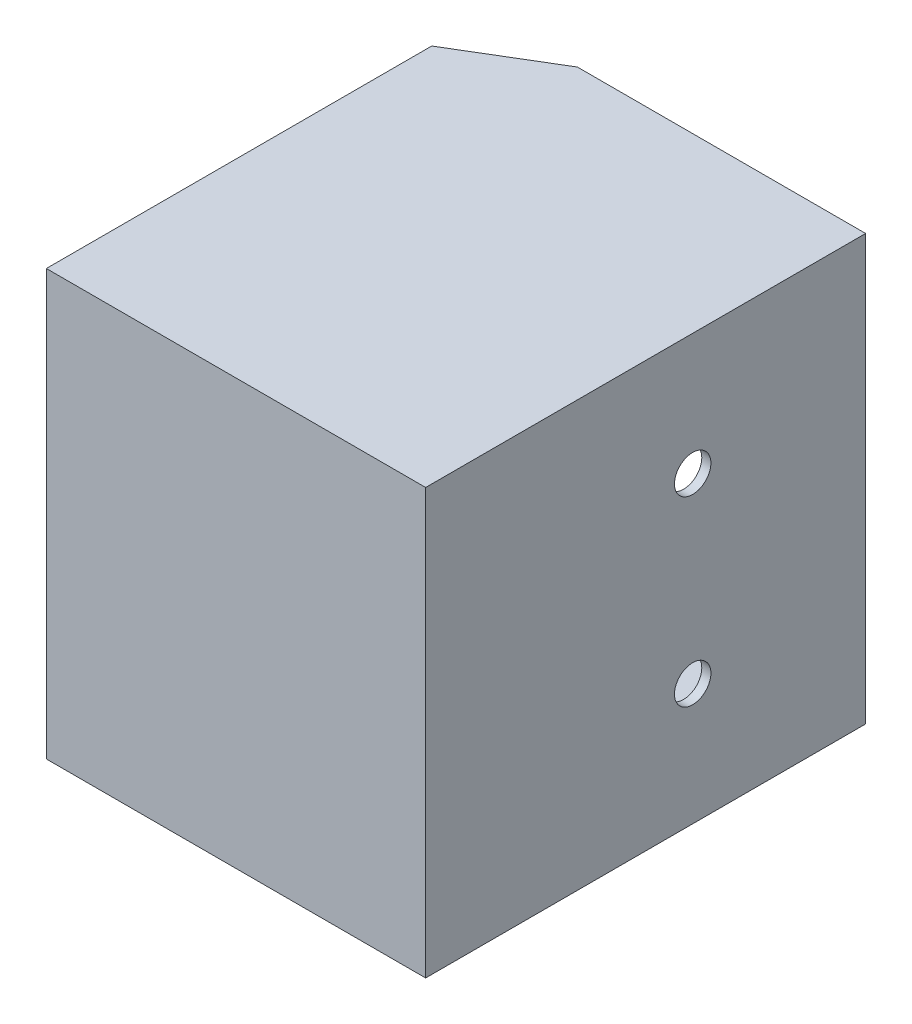
SolidWorks part; units mm, degrees
ref_plane "Front Plane" through (0, 0, 0) normal (0, 0, 1) x (1, 0, 0)
ref_plane "Top Plane" through (0, 0, 0) normal (0, 1, 0) x (1, 0, 0)
ref_plane "Right Plane" through (0, 0, 0) normal (1, 0, 0) x (0, 0, -1)
ref_plane "PL_Front_base" through (67, 0, 0) normal (1, 0, 0) x (0, 0, -1)
sketch "SK_Front" plane through (67, 0, 0) normal (1, 0, 0) x (0, 0, -1)
  line L0 (15, -70) -> (15, 70)
  line L1 (15, 70) -> (-130, 70)
  line L2 (-130, 70) -> (-130, -70)
  line L3 (-130, -70) -> (15, -70)
  circle A0 centre (-42, 30) radius 6
  circle A1 centre (-42, -30) radius 6
  dimension "D9_SK_Front" = 12
  dimension "D12_SK_Front" = 12
  dimension "P1" = 15
  dimension "P2" = 70
  dimension "P3" = 15
  dimension "P4" = 70
  dimension "P5" = 130
  dimension "P6" = 70
  dimension "P7" = 130
  dimension "P8" = 70
  dimension "P10" = 42
  dimension "P11" = 30
  dimension "P13" = 42
  dimension "P14" = 30
extrude "Front" add sketch "SK_Front" along normal blind 3
ref_plane "PL_Back_base" through (-55, 0, 0) normal (1, 0, 0) x (0, 0, -1)
sketch "SK_Back" plane through (-55, 0, 0) normal (1, 0, 0) x (0, 0, -1)
  line L0 (-3, -70) -> (-3, 70)
  line L1 (-3, 70) -> (-130, 70)
  line L2 (-130, 70) -> (-130, -70)
  line L3 (-130, -70) -> (-3, -70)
  dimension "P1" = 3
  dimension "P2" = 70
  dimension "P3" = 3
  dimension "P4" = 70
  dimension "P5" = 130
  dimension "P6" = 70
  dimension "P7" = 130
  dimension "P8" = 70
extrude "Back" add sketch "SK_Back" along normal blind 3
ref_plane "PL_Top_base" through (0, 0, 127) normal (0, 0, 1) x (1, 0, 0)
sketch "SK_Top" plane through (0, 0, 127) normal (0, 0, 1) x (1, 0, 0)
  line L0 (-55, -70) -> (70, -70)
  line L1 (70, -70) -> (70, 70)
  line L2 (70, 70) -> (-55, 70)
  line L3 (-55, 70) -> (-55, -70)
  dimension "P1" = 55
  dimension "P2" = 70
  dimension "P3" = 70
  dimension "P4" = 70
  dimension "P5" = 70
  dimension "P6" = 70
  dimension "P7" = 55
  dimension "P8" = 70
extrude "Top" add sketch "SK_Top" along normal blind 3
ref_plane "PL_Side_L_base" through (0, 67, 0) normal (0, 1, 0) x (1, 0, 0)
sketch "SK_Side_L" plane through (0, 67, 0) normal (0, 1, 0) x (1, 0, 0)
  line L0 (-25, 15) -> (70, 15)
  line L1 (70, 15) -> (70, -130)
  line L2 (70, -130) -> (-55, -130)
  line L3 (-55, -130) -> (-55, -3)
  line L4 (-55, -3) -> (-25, 15)
  dimension "P1" = 25
  dimension "P2" = 15
  dimension "P3" = 70
  dimension "P4" = 15
  dimension "P5" = 70
  dimension "P6" = 130
  dimension "P7" = 55
  dimension "P8" = 130
  dimension "P9" = 55
  dimension "P10" = 3
extrude "Side_L" add sketch "SK_Side_L" along normal blind 3
ref_plane "PL_Side_R_base" through (0, -70, 0) normal (0, 1, 0) x (1, 0, 0)
sketch "SK_Side_R" plane through (0, -70, 0) normal (0, 1, 0) x (1, 0, 0)
  line L0 (-25, 15) -> (70, 15)
  line L1 (70, 15) -> (70, -130)
  line L2 (70, -130) -> (-55, -130)
  line L3 (-55, -130) -> (-55, -3)
  line L4 (-55, -3) -> (-25, 15)
  dimension "P1" = 25
  dimension "P2" = 15
  dimension "P3" = 70
  dimension "P4" = 15
  dimension "P5" = 70
  dimension "P6" = 130
  dimension "P7" = 55
  dimension "P8" = 130
  dimension "P9" = 55
  dimension "P10" = 3
extrude "Side_R" add sketch "SK_Side_R" along normal blind 3
ref_plane "PL_Horn_Plate_base" through (0, 20.5, 0) normal (0, 1, 0) x (1, 0, 0)
sketch "SK_Horn_Plate" plane through (0, 20.5, 0) normal (0, 1, 0) x (1, 0, 0)
  line L0 (-20, 12) -> (40, 12)
  line L1 (40, 12) -> (40, -130)
  line L2 (40, -130) -> (-20, -130)
  line L3 (-20, -130) -> (-20, 12)
  circle A0 centre (0, 0) radius 2
  dimension "D9_SK_Horn_Plate" = 4
  dimension "P1" = 20
  dimension "P2" = 12
  dimension "P3" = 40
  dimension "P4" = 12
  dimension "P5" = 40
  dimension "P6" = 130
  dimension "P7" = 20
  dimension "P8" = 130
extrude "Horn_Plate" add sketch "SK_Horn_Plate" along normal blind 4
equation "\"Head_top_z\" = 130"
equation "\"Head_chamfer_x\" = -25"
equation "\"Head_chamfer_z\" = 3"
